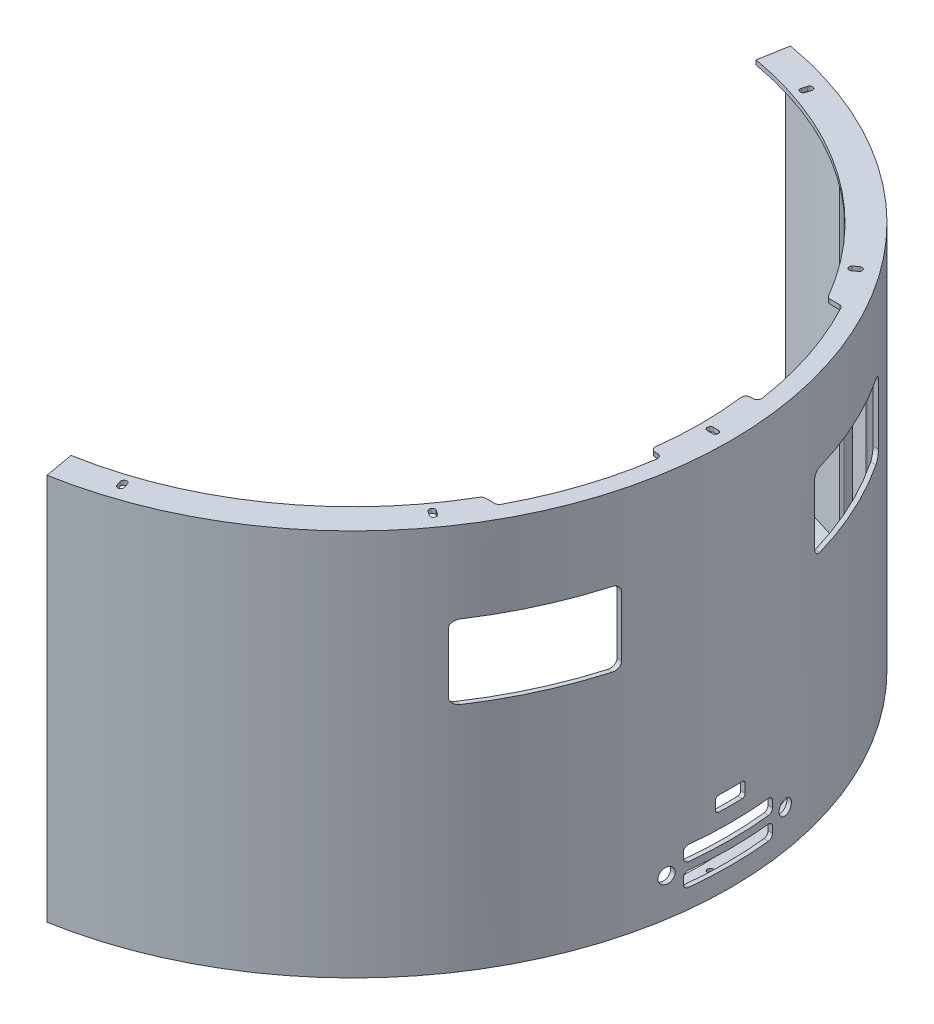
SolidWorks part; units mm, degrees
ref_plane "Front Plane" through (0, 0, 0) normal (0, 0, 1) x (1, 0, 0)
ref_plane "Top Plane" through (0, 0, 0) normal (0, 1, 0) x (1, 0, 0)
ref_plane "Right Plane" through (0, 0, 0) normal (1, 0, 0) x (0, 0, -1)
sketch "Sketch3" plane through (0, 0, 0) normal (0, 1, 0) x (1, 0, 0)
  line L0 (0, -251.5) -> (0, 251.5)
  line L1 (-44.1935, 250.6336) -> (-43.6725, 247.6791)
  line L2 (-43.6725, -247.6791) -> (-44.1935, -250.6336)
  arc A0 (0, 251.5) -> (0, -251.5) centre (0, 0) cw
  arc A1 (0, 251.5) -> (-43.6725, 247.6791) centre (0, 0) ccw
  arc A2 (0, -251.5) -> (-43.6725, -247.6791) centre (0, 0) cw
  arc A3 (0, 254.5) -> (0, -254.5) centre (0, 0) cw
  arc A4 (0, 254.5) -> (-44.1935, 250.6336) centre (0, 0) ccw
  arc A5 (0, -254.5) -> (-44.1935, -250.6336) centre (0, 0) cw
  point P4 (0, 0)
  dimension "D1" = 503
  dimension "D2" = 3
  dimension "D3" = 3
  dimension "D4" = 3
extrude "Boss-Extrude1" add sketch "Sketch3" along normal blind 255 contours A5 A3 A4 L1 A1 A0 A2 L2
sketch "Sketch6" plane through (0, 255, 0) normal (0, 1, 0) x (1, 0, 0)
  line L0 (0, -256) -> (0, 256)
  line L1 (-2, 253.0819) -> (-2, 247.0819)
  line L2 (-1, 246.0819) -> (1, 246.0819)
  line L3 (2, 247.0819) -> (2, 253.0819)
  line L4 (-2, 253.0819) -> (2, 253.0819)
  line L54 (108.0062, 228.8867) -> (105.4029, 223.4809)
  line L55 (105.87, 222.146) -> (107.6719, 221.2783)
  line L56 (109.0068, 221.7454) -> (111.6101, 227.1512)
  line L57 (108.0062, 228.8867) -> (111.6101, 227.1512)
  line L58 (196.6204, 159.3577) -> (191.9294, 155.6167)
  line L59 (191.7711, 154.2114) -> (193.0181, 152.6477)
  line L60 (194.4234, 152.4894) -> (199.1144, 156.2303)
  line L61 (196.6204, 159.3577) -> (199.1144, 156.2303)
  line L62 (246.2916, 58.2659) -> (240.442, 56.9308)
  line L63 (239.6896, 55.7333) -> (240.1347, 53.7835)
  line L64 (241.3321, 53.031) -> (247.1817, 54.3662)
  line L65 (246.2916, 58.2659) -> (247.1817, 54.3662)
  line L66 (247.1817, -54.3662) -> (241.3321, -53.031)
  line L67 (240.1347, -53.7835) -> (239.6896, -55.7333)
  line L68 (240.442, -56.9308) -> (246.2916, -58.2659)
  line L69 (247.1817, -54.3662) -> (246.2916, -58.2659)
  line L70 (199.1144, -156.2303) -> (194.4234, -152.4894)
  line L71 (193.0181, -152.6477) -> (191.7711, -154.2114)
  line L72 (191.9294, -155.6167) -> (196.6204, -159.3577)
  line L73 (199.1144, -156.2303) -> (196.6204, -159.3577)
  line L74 (111.6101, -227.1512) -> (109.0068, -221.7454)
  line L75 (107.6719, -221.2783) -> (105.87, -222.146)
  line L76 (105.4029, -223.4809) -> (108.0062, -228.8867)
  line L77 (111.6101, -227.1512) -> (108.0062, -228.8867)
  line L78 (2, -253.0819) -> (2, -247.0819)
  line L79 (1, -246.0819) -> (-1, -246.0819)
  line L80 (-2, -247.0819) -> (-2, -253.0819)
  line L81 (2, -253.0819) -> (-2, -253.0819)
  arc A2 (2, 247.0819) -> (1, 246.0819) centre (1, 247.0819) cw
  arc A3 (-2, 247.0819) -> (-1, 246.0819) centre (-1, 247.0819) ccw
  arc A26 (109.0068, 221.7454) -> (107.6719, 221.2783) centre (108.1058, 222.1792) cw
  arc A27 (105.4029, 223.4809) -> (105.87, 222.146) centre (106.3039, 223.047) ccw
  arc A28 (194.4234, 152.4894) -> (193.0181, 152.6477) centre (193.7999, 153.2712) cw
  arc A29 (191.9294, 155.6167) -> (191.7711, 154.2114) centre (192.5529, 154.8349) ccw
  arc A30 (241.3321, 53.031) -> (240.1347, 53.7835) centre (241.1096, 54.006) cw
  arc A31 (240.442, 56.9308) -> (239.6896, 55.7333) centre (240.6645, 55.9558) ccw
  arc A32 (240.442, -56.9308) -> (239.6896, -55.7333) centre (240.6645, -55.9558) cw
  arc A33 (241.3321, -53.031) -> (240.1347, -53.7835) centre (241.1096, -54.006) ccw
  arc A34 (191.9294, -155.6167) -> (191.7711, -154.2114) centre (192.5529, -154.8349) cw
  arc A35 (194.4234, -152.4894) -> (193.0181, -152.6477) centre (193.7999, -153.2712) ccw
  arc A36 (105.4029, -223.4809) -> (105.87, -222.146) centre (106.3039, -223.047) cw
  arc A37 (109.0068, -221.7454) -> (107.6719, -221.2783) centre (108.1058, -222.1792) ccw
  arc A38 (-2, -247.0819) -> (-1, -246.0819) centre (-1, -247.0819) cw
  arc A39 (2, -247.0819) -> (1, -246.0819) centre (1, -247.0819) ccw
  point P9 (0, 0)
  point P19 (2, 246.0819)
  point P22 (-2, 246.0819)
  point P23 (0, 246.0819)
  point P59 (0, 0)
  point P68 (0, 0)
  point P76 (0, 0)
  dimension "D3" = 1
  dimension "D1" = 7
  dimension "D2" = 4
  dimension "D4" = 0
  dimension "D5" = 7
  dimension "D6" = 256
  dimension "D7" = 8
extrude "Boss-Extrude2" add sketch "Sketch6" against normal blind 255 separate body
combine bodies "Combine2" operation type add bodies to combine 109 101 115 116 117 118 119 120 121
sketch "Sketch7" plane through (0, 255, 0) normal (0, 1, 0) x (1, 0, 0)
  line L0 (-44.1935, 250.6336) -> (-40.7205, 230.9374)
  line L1 (-44.1935, -250.6336) -> (-40.7205, -230.9374)
  arc A0 (-40.7205, 230.9374) -> (-40.7205, -230.9374) centre (0, 0) cw
  arc A2 (-44.1935, 250.6336) -> (-44.1935, -250.6336) centre (0, 0) cw
  arc A3 (-44.1935, -250.6336) -> (-44.1935, 250.6336) centre (0, 0) ccw construction
extrude "Boss-Extrude3" add sketch "Sketch7" along normal blind 3 contours A2 L0 A0 L1
sketch "Sketch8" plane through (0, 255, 0) normal (0, -1, 0) x (1, 0, 0)
  line L0 (240.8, 0) -> (244.2, 0) construction
  line L1 (240.8, 2) -> (244.2, 2)
  line L2 (240.8, -2) -> (244.2, -2)
  line L3 (194.8113, -141.5387) -> (197.562, -143.5372) construction
  line L12 (195.9869, -139.9207) -> (198.7375, -141.9191)
  line L21 (193.6357, -143.1567) -> (196.3864, -145.1552)
  line L24 (74.4113, -229.0144) -> (75.462, -232.248) construction
  line L27 (76.3134, -228.3964) -> (77.3641, -231.63)
  line L28 (72.5092, -229.6324) -> (73.5598, -232.866)
  line L29 (-74.4113, -229.0144) -> (-75.462, -232.248) construction
  line L30 (-72.5092, -229.6324) -> (-73.5598, -232.866)
  line L31 (-76.3134, -228.3964) -> (-77.3641, -231.63)
  line L32 (-194.8113, -141.5387) -> (-197.562, -143.5372) construction
  line L33 (-193.6357, -143.1567) -> (-196.3864, -145.1552)
  line L34 (-195.9869, -139.9207) -> (-198.7375, -141.9191)
  line L35 (-240.8, 0) -> (-244.2, 0) construction
  line L36 (-240.8, -2) -> (-244.2, -2)
  line L37 (-240.8, 2) -> (-244.2, 2)
  line L38 (-194.8113, 141.5387) -> (-197.562, 143.5372) construction
  line L39 (-195.9869, 139.9207) -> (-198.7375, 141.9191)
  line L40 (-193.6357, 143.1567) -> (-196.3864, 145.1552)
  line L41 (-74.4113, 229.0144) -> (-75.462, 232.248) construction
  line L42 (-76.3134, 228.3964) -> (-77.3641, 231.63)
  line L43 (-72.5092, 229.6324) -> (-73.5598, 232.866)
  line L44 (74.4113, 229.0144) -> (75.462, 232.248) construction
  line L45 (72.5092, 229.6324) -> (73.5598, 232.866)
  line L46 (76.3134, 228.3964) -> (77.3641, 231.63)
  line L47 (194.8113, 141.5387) -> (197.562, 143.5372) construction
  line L48 (193.6357, 143.1567) -> (196.3864, 145.1552)
  line L49 (195.9869, 139.9207) -> (198.7375, 141.9191)
  circle A1 centre (242.5, 0) radius 1.7 construction
  arc A2 (240.8, 2) -> (240.8, -2) centre (240.8, 0) ccw
  arc A3 (244.2, -2) -> (244.2, 2) centre (244.2, 0) ccw
  arc A24 (195.9869, -139.9207) -> (193.6357, -143.1567) centre (194.8113, -141.5387) ccw
  arc A25 (196.3864, -145.1552) -> (198.7375, -141.9191) centre (197.562, -143.5372) ccw
  arc A26 (76.3134, -228.3964) -> (72.5092, -229.6324) centre (74.4113, -229.0144) ccw
  arc A27 (73.5598, -232.866) -> (77.3641, -231.63) centre (75.462, -232.248) ccw
  arc A28 (-72.5092, -229.6324) -> (-76.3134, -228.3964) centre (-74.4113, -229.0144) ccw
  arc A29 (-77.3641, -231.63) -> (-73.5598, -232.866) centre (-75.462, -232.248) ccw
  arc A30 (-193.6357, -143.1567) -> (-195.9869, -139.9207) centre (-194.8113, -141.5387) ccw
  arc A31 (-198.7375, -141.9191) -> (-196.3864, -145.1552) centre (-197.562, -143.5372) ccw
  arc A32 (-240.8, -2) -> (-240.8, 2) centre (-240.8, 0) ccw
  arc A33 (-244.2, 2) -> (-244.2, -2) centre (-244.2, 0) ccw
  arc A34 (-195.9869, 139.9207) -> (-193.6357, 143.1567) centre (-194.8113, 141.5387) ccw
  arc A35 (-196.3864, 145.1552) -> (-198.7375, 141.9191) centre (-197.562, 143.5372) ccw
  arc A36 (-76.3134, 228.3964) -> (-72.5092, 229.6324) centre (-74.4113, 229.0144) ccw
  arc A37 (-73.5598, 232.866) -> (-77.3641, 231.63) centre (-75.462, 232.248) ccw
  arc A38 (72.5092, 229.6324) -> (76.3134, 228.3964) centre (74.4113, 229.0144) ccw
  arc A39 (77.3641, 231.63) -> (73.5598, 232.866) centre (75.462, 232.248) ccw
  arc A40 (193.6357, 143.1567) -> (195.9869, 139.9207) centre (194.8113, 141.5387) ccw
  arc A41 (198.7375, 141.9191) -> (196.3864, 145.1552) centre (197.562, 143.5372) ccw
  point P6 (242.5, 0)
  point P16 (196.1866, -142.5379)
  point P23 (74.9366, -230.6312)
  point P28 (0, 0)
  point P31 (-74.9366, -230.6312)
  point P35 (0, 0)
  point P39 (-196.1866, -142.5379)
  point P44 (0, 0)
  point P47 (-242.5, 0)
  point P54 (-196.1866, 142.5379)
  point P57 (0, 0)
  point P62 (-74.9366, 230.6312)
  point P69 (74.9366, 230.6312)
  point P76 (196.1866, 142.5379)
  point P81 (0, 0)
  dimension "D1" = 2
extrude "Cut-Extrude3" cut sketch "Sketch8" against normal blind 5
pattern_linear "LPattern1" count 2 spacing 258 along (0, -1, 0) of "Boss-Extrude3"
pattern_linear "LPattern2" count 2 spacing 258 along (0, -1, 0) of "Cut-Extrude3"
sketch "Sketch11" plane through (0, 258, 0) normal (0, 1, 0) x (1, 0, 0)
  line L0 (-44.1935, 250.6336) -> (0, 0)
  line L1 (0, 0) -> (44.1935, 250.6336)
  line L2 (-117.5787, 0) -> (117.5787, 0) construction
  arc A0 (-44.1935, 250.6336) -> (44.1935, 250.6336) centre (0, 0) cw
extrude "Cut-Extrude7" cut sketch "Sketch11" against normal blind 324
mirror "Mirror1" about plane through (0, 0, 0) normal (0, 0, 1) of "Cut-Extrude7"
sketch "Sketch13" plane through (0, 258, 0) normal (0, 1, 0) x (1, 0, 0)
  line L3 (240.8, 32.1355) -> (189.8429, 32.1355)
  line L4 (189.8429, 32.1355) -> (189.8429, 116.171)
  line L5 (189.8429, 116.171) -> (213.358, 116.171)
  line L6 (-117.5787, 0) -> (117.5787, 0) construction
  line L7 (189.8429, -116.171) -> (213.358, -116.171)
  line L8 (189.8429, -32.1355) -> (189.8429, -116.171)
  line L9 (240.8, -32.1355) -> (189.8429, -32.1355)
  arc A0 (240.8, 32.1355) -> (213.358, 116.171) centre (0, 0) ccw
  arc A1 (240.8, -32.1355) -> (213.358, -116.171) centre (0, 0) cw
extrude "Cut-Extrude10" cut sketch "Sketch13" against normal blind 5
fillet "Fillet2" radius 3 8 edges at (203.7021, 256.5, 116.171) (213.358, 256.5, 116.171) (232.2877, 256.5, 32.1355) (240.8, 256.5, 32.1355) (232.2877, 256.5, -32.1355) (240.8, 256.5, -32.1355) (213.358, 256.5, -116.171) (203.7021, 256.5, -116.171)
sketch "Sketch14" plane through (0, 0, 0) normal (1, 0, 0) x (0, 0, -1)
  line L1 (-140, 153) -> (-70, 153)
  line L2 (-145, 158) -> (-145, 198)
  line L3 (-140, 203) -> (-70, 203)
  line L4 (-65, 158) -> (-65, 198)
  line L5 (-145, 153) -> (-65, 203) construction
  line L6 (-145, 203) -> (-65, 153) construction
  line L8 (-57.9121, 0) -> (-155.2391, 0) construction
  arc A0 (-140, 203) -> (-145, 198) centre (-140, 198) ccw
  arc A1 (-145, 158) -> (-140, 153) centre (-140, 158) ccw
  arc A2 (-70, 153) -> (-65, 158) centre (-70, 158) ccw
  arc A3 (-70, 203) -> (-65, 198) centre (-70, 198) cw
  point P0 (-105, 178)
  dimension "D5" = 5
  dimension "D1" = 80
  dimension "D2" = 50
  dimension "D3" = 178
  dimension "D4" = 105
extrude "Cut-Extrude11" cut sketch "Sketch14" along normal blind 317
mirror "Mirror2" about plane through (0, 0, 0) normal (0, 0, 1) of "Cut-Extrude11"
sketch "Sketch15" plane through (0, 0, 0) normal (1, 0, 0) x (0, 0, -1)
  line L0 (-27, 10) -> (27, 10)
  line L1 (-27, 25) -> (27, 25)
  line L2 (-30, 28) -> (-30, 32)
  line L3 (-27, 35) -> (27, 35)
  line L4 (30, 28) -> (30, 32)
  line L5 (-30, 25) -> (30, 35) construction
  line L6 (-30, 35) -> (30, 25) construction
  line L7 (-30, 13) -> (-30, 17)
  line L8 (-27, 20) -> (27, 20)
  line L9 (30, 13) -> (30, 17)
  line L10 (-30, 10) -> (30, 20) construction
  line L11 (-30, 20) -> (30, 10) construction
  line L12 (0, 117.5787) -> (0, -117.5787) construction
  line L14 (-8, 45) -> (8, 45)
  line L15 (-10, 47) -> (-10, 53)
  line L16 (-8, 55) -> (8, 55)
  line L17 (10, 47) -> (10, 53)
  line L18 (-10, 45) -> (10, 55) construction
  line L19 (-10, 55) -> (10, 45) construction
  arc A0 (-27, 25) -> (-30, 28) centre (-27, 28) cw
  arc A1 (-30, 32) -> (-27, 35) centre (-27, 32) cw
  arc A2 (27, 25) -> (30, 28) centre (27, 28) ccw
  arc A3 (27, 35) -> (30, 32) centre (27, 32) cw
  arc A4 (-27, 10) -> (-30, 13) centre (-27, 13) cw
  arc A5 (-30, 17) -> (-27, 20) centre (-27, 17) cw
  arc A6 (27, 10) -> (30, 13) centre (27, 13) ccw
  arc A7 (27, 20) -> (30, 17) centre (27, 17) cw
  circle A8 centre (40, 22.5) radius 5
  circle A9 centre (-40, 22.5) radius 5
  arc A10 (-8, 45) -> (-10, 47) centre (-8, 47) cw
  arc A11 (-10, 53) -> (-8, 55) centre (-8, 53) cw
  arc A12 (8, 45) -> (10, 47) centre (8, 47) ccw
  arc A13 (8, 55) -> (10, 53) centre (8, 53) cw
  point P0 (0, 30)
  point P20 (0, 15)
  point P41 (0, 50)
  dimension "D5" = 3
  dimension "D8" = 2.5
  dimension "D13" = 2
  dimension "D1" = 60
  dimension "D2" = 0
  dimension "D3" = 30
  dimension "D4" = 10
  dimension "D7" = 15
  dimension "D9" = 40
  dimension "D10" = 10
  dimension "D11" = 20
  dimension "D12" = 20
  dimension "D6" = 2
extrude "Cut-Extrude12" cut sketch "Sketch15" along normal blind 368
